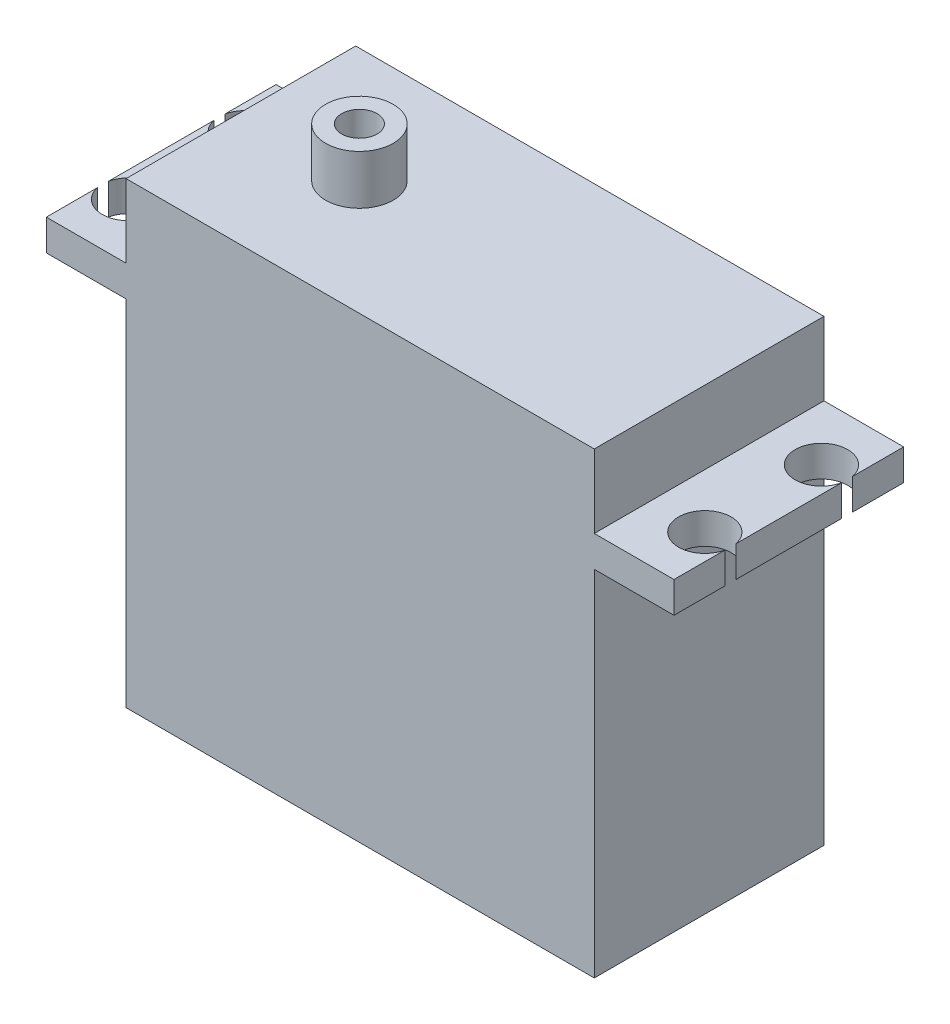
SolidWorks part; units mm, degrees
ref_plane "Front Plane" through (0, 0, 0) normal (0, 0, 1) x (1, 0, 0)
ref_plane "Top Plane" through (0, 0, 0) normal (0, 1, 0) x (1, 0, 0)
ref_plane "Right Plane" through (0, 0, 0) normal (1, 0, 0) x (0, 0, -1)
sketch "Sketch1" plane through (0, 0, 0) normal (0, 1, 0) x (1, 0, 0)
  line L1 (-20.1422, -9.8806) -> (20.1422, -9.8806)
  line L2 (-20.1422, -9.8806) -> (-20.1422, 9.8806)
  line L3 (-20.1422, 9.8806) -> (20.1422, 9.8806)
  line L4 (20.1422, -9.8806) -> (20.1422, 9.8806)
  point P4 (-20.1422, 0)
  point P7 (0, 9.8806)
  dimension "D1" = 19.7612
  dimension "D2" = 40.2844
extrude "Boss-Extrude1" add sketch "Sketch1" along normal blind 39.4208
sketch "Sketch2" plane through (20.1422, 0, 0) normal (1, 0, 0) x (0, 0, -1)
  line L0 (-9.8806, 39.4208) -> (-9.8806, 0) construction
  line L1 (-9.8806, 30.4546) -> (9.8806, 30.4546)
  line L2 (-9.8806, 30.4546) -> (-9.8806, 33.1216)
  line L3 (-9.8806, 33.1216) -> (9.8806, 33.1216)
  line L4 (9.8806, 30.4546) -> (9.8806, 33.1216)
  line L5 (9.8806, 39.4208) -> (9.8806, 0) construction
  line L6 (-9.8806, 39.4208) -> (9.8806, 39.4208) construction
  dimension "D1" = 2.667
  dimension "D2" = 6.2992
extrude "Boss-Extrude2" add sketch "Sketch2" along normal blind 6.858
sketch "Sketch3" plane through (0, 33.1216, 0) normal (0, 1, 0) x (1, 0, 0)
  line L0 (27.0002, 0) -> (0, 0) construction
  line L1 (27.0002, 9.8806) -> (27.0002, -9.8806) construction
  line L4 (20.1422, -9.8806) -> (20.1422, 9.8806) construction
  circle A0 centre (24.7904, 5.0165) radius 2.2606
  circle A1 centre (24.7904, -5.0165) radius 2.2606
  point P7 (24.7904, 2.7559)
  point P11 (22.5298, 5.0165)
  dimension "D1" = 4.5212
  dimension "D2" = 5.5118
  dimension "D3" = 2.3876
extrude "Cut-Extrude2" cut sketch "Sketch3" against normal through all
mirror "Mirror1" about plane through (0, 0, 0) normal (1, 0, 0) of "Cut-Extrude2", "Boss-Extrude2"
sketch "Sketch4" plane through (0, 39.4208, 0) normal (0, 1, 0) x (1, 0, 0)
  line L0 (20.1422, -9.8806) -> (20.1422, 9.8806) construction
  circle A0 centre (-9.9441, 0) radius 2.9083
  point P2 (-7.0358, 0)
  point P5 (0, 0)
  point P7 (0, 0)
  dimension "D2" = 5.8166
  dimension "D1" = 27.178
extrude "Boss-Extrude3" add sketch "Sketch4" along normal blind 4.2418
sketch "Sketch5" plane through (0, 43.6626, 0) normal (0, 1, 0) x (1, 0, 0)
  circle A0 centre (-9.9441, 0) radius 1.524
  dimension "D1" = 3.048
extrude "Cut-Extrude3" cut sketch "Sketch5" against normal blind 7.4422
